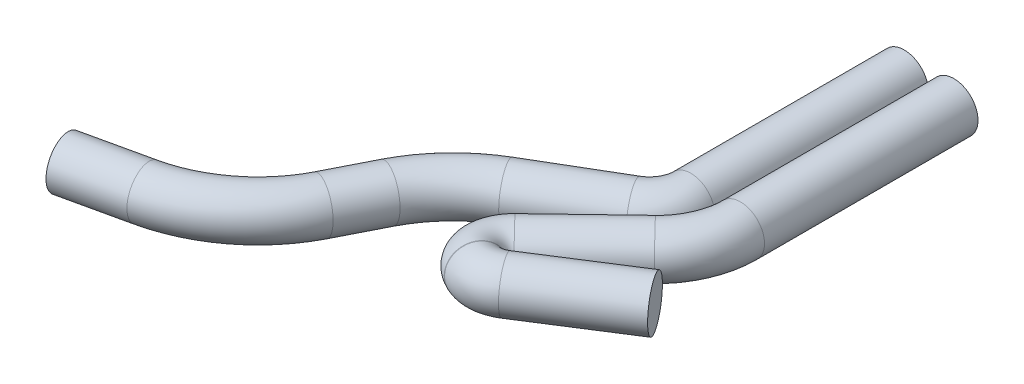
SolidWorks part; units mm, degrees
ref_plane "Plan de face" through (0, 0, 0) normal (0, 0, 1) x (1, 0, 0)
ref_plane "Plan de dessus" through (0, 0, 0) normal (0, 1, 0) x (1, 0, 0)
ref_plane "Plan de droite" through (0, 0, 0) normal (1, 0, 0) x (0, 0, -1)
sketch "Esquisse1" plane through (0, 0, 0) normal (0, 0, 1) x (1, 0, 0)
  line L0 (-1.8, 0) -> (1.8, 0) construction
  circle A0 centre (-1.8, 0) radius 1.75
  circle A1 centre (1.8, 0) radius 1.75
  dimension "D1" = 3.5
  dimension "D2" = 3.6
extrude "Boss.-Extru.1" add sketch "Esquisse1" along normal blind 5 and the other way blind 10
sketch3d "Esquisse3D1"
  line L0 (-27.1738, 2.5, 26.7093) -> (-27.282, 2.5, 26.2212) construction
  line L1 (-27.1738, 2.5, 26.7093) -> (-34.9842, 2.5, 28.4409) construction
  line L2 (11.0981, 2.5, 8.82) -> (4.351, 2.5, 13.1184)
  line L3 (4.351, -1.5, 13.1184) -> (11.0981, -1.5, 8.82)
  line L4 (4.6196, 2.5, 13.5401) -> (4.351, 2.5, 13.1184) construction
  line L5 (11.0981, -1.5, 8.82) -> (11.0981, 2.5, 8.82) construction
  line L6 (11.3667, -1.5, 9.2417) -> (4.6196, -1.5, 13.5401)
  line L7 (4.6196, 2.5, 13.5401) -> (11.3667, 2.5, 9.2417)
  line L8 (4.351, -1.5, 13.1184) -> (11.0981, -1.5, 8.82) construction
  line L9 (11.3667, -1.5, 9.2417) -> (4.6196, -1.5, 13.5401) construction
  line L10 (-35.0924, 2.5, 27.9527) -> (-27.282, 2.5, 26.2212)
  line L11 (-27.282, -1.5, 26.2212) -> (-35.0924, -1.5, 27.9527)
  line L14 (-34.9842, -1.5, 28.4409) -> (-27.1738, -1.5, 26.7093)
  line L15 (-27.1738, 2.5, 26.7093) -> (-34.9842, 2.5, 28.4409)
  arc A0 (-27.1738, -1.5, 26.7093) -> (-27.1738, 2.5, 26.7093) centre (-29.3568, 0.5, 27.1933) ccw construction
  arc A1 (4.351, 2.5, 13.1184) -> (4.351, -1.5, 13.1184) centre (6.2368, 0.5, 11.9169) ccw
  arc A2 (-27.282, 2.5, 26.2212) -> (-27.282, -1.5, 26.2212) centre (-29.4651, 0.5, 26.7052) ccw construction
  arc A3 (4.6196, 2.5, 13.5401) -> (4.6196, -1.5, 13.5401) centre (6.5055, 0.5, 12.3386) ccw
  arc A4 (4.6196, 2.5, 13.5401) -> (4.6196, -1.5, 13.5401) centre (6.5055, 0.5, 12.3386) ccw construction
  arc A5 (-27.282, 2.5, 26.2212) -> (-27.282, -1.5, 26.2212) centre (-29.4651, 0.5, 26.7052) ccw
  arc A6 (4.351, 2.5, 13.1184) -> (4.351, -1.5, 13.1184) centre (6.2368, 0.5, 11.9169) ccw construction
  arc A7 (-27.1738, -1.5, 26.7093) -> (-27.1738, 2.5, 26.7093) centre (-29.3568, 0.5, 27.1933) ccw
  arc A8 (11.0981, -1.5, 8.82) -> (11.6501, -1.5, 8.7717) centre (11.4205, -1.5, 9.326) ccw construction
  point P5 (7.8487, 0.5, 14.4471)
  point P11 (8.1174, 0.5, 14.8688)
  point P17 (-30.1144, 0.5, 23.7763)
  point P24 (-28.7075, 0.5, 30.1222)
  point P35 (-28.7075, 0.5, 30.1222)
  point P42 (-30.1144, 0.5, 23.7763)
  point P46 (8.1174, 0.5, 14.8688)
  point P50 (7.8487, 0.5, 14.4471)
  point P61 (11.4205, -2.1, 9.326)
sketch3d "Esquisse3D2"
  line L0 (1.8, 0, 5.5) -> (1.8, 0, 5)
  line L1 (6.2368, 0.5, 11.9169) -> (6.5055, 0.5, 12.3386) construction
  line L2 (6.3712, 0.5, 12.1278) -> (-2.7727, 0.5, 17.9531)
  line L3 (4.6196, 2.5, 13.5401) -> (11.3667, 2.5, 9.2417) construction
  line L4 (-4.8168, 0.3486, 18.0224) -> (-4.7698, 0.3552, 18.0468)
  line L5 (-0.0504, 0, 9.8337) -> (-5.2592, 0, 14.8212)
  line L6 (-4.2, 0, 5.5) -> (-0.0504, 0, 9.8337) construction
  line L7 (-4.2, 0, 5.5) -> (1.8, 0, 5.5) construction
  circle A0 centre (1.8, 0, 5) radius 1.75 construction
  arc A1 (-0.0504, 0, 9.8337) -> (1.8, 0, 5.5) centre (-4.2, 0, 5.5) ccw
  arc A2 (-2.7727, 0.5, 17.9531) -> (-4.7698, 0.3552, 18.0468) centre (-3.8361, 0.2118, 16.2839) ccw
  arc A3 (-4.8168, 0.3486, 18.0224) -> (-5.2592, 0, 14.8212) centre (-3.8881, 0.2639, 16.2531) ccw
  point P4 (1.8, 0, 6.75)
  point P17 (-4.2, 6, 5.5)
  point P19 (-3.7495, 0.5, 18.5754)
  point P20 (-3.6812, -1.7674, 16.527)
  point P23 (-7.2733, 0, 16.7497)
  point P24 (-3.7056, -1.7186, 16.4438)
  dimension "D1" = 6
  dimension "D2" = 12
  dimension "D4" = 4
  dimension "D6" = 2
  dimension "D3" = 0.5
  dimension "D5" = 10
sketch "Esquisse2" plane through (0, 0, 5) normal (0, 0, 1) x (1, 0, 0)
  circle A1 centre (1.8, 0) radius 1.75
  circle A2 centre (1.8, 0) radius 1.75
  dimension "D1" = 0
sweep "Balayage1" add profiles "Esquisse2" path "Esquisse3D2"
sketch "Esquisse3" plane through (-0.9639, 0, 0.6141) normal (0.8434, 0, -0.5373) x (-0.5373, 0, -0.8434)
  circle A1 centre (-13.6517, 0.5) radius 1.75
  circle A2 centre (-13.6517, 0.5) radius 1.75
  dimension "D1" = 0
extrude "Enlèv. mat.-Extru.1" cut sketch "Esquisse3" against normal blind 3
sketch3d "Esquisse3D3"
  line L0 (-1.8, 0, 5) -> (-1.8, 0, 5.5)
  line L1 (-3.2777, 0, 8.0851) -> (-9.1074, 0, 11.5182)
  line L2 (-29.3568, 0.5, 27.1933) -> (-29.4651, 0.5, 26.7052) construction
  line L3 (-29.411, 0.5, 26.9492) -> (-21.673, 0.5, 25.2338)
  line L4 (-35.0924, 2.5, 27.9527) -> (-27.282, 2.5, 26.2212) construction
  line L5 (-14.679, 0.2886, 19.4943) -> (-13.1949, 0.1348, 16.1179)
  circle A0 centre (-1.8, 0, 5) radius 1.75 construction
  arc A1 (-3.2777, 0, 8.0851) -> (-1.8, 0, 5.5) centre (-4.8, 0, 5.5) ccw
  arc A2 (-13.1949, 0.1348, 16.1179) -> (-9.1074, 0, 11.5182) centre (-4.0459, 0.7115, 20.1132) ccw
  arc A3 (-21.673, 0.5, 25.2338) -> (-14.679, 0.2886, 19.4943) centre (-23.8345, -0.0163, 15.4838) ccw
  point P4 (-1.8, 0, 6.75)
  point P8 (-1.8, 0, 7.2149)
  point P9 (-4.8, 3, 5.5)
  point P20 (-11.8945, 0, 13.1595)
  point P21 (-3.6848, -9.2632, 20.7263)
  point P24 (-16.7191, 0.5, 24.1355)
  point P25 (-23.9463, 9.9704, 14.9798)
  dimension "D1" = 3
  dimension "D6" = 10
  dimension "D7" = 10
  dimension "D2" = 0.5
  dimension "D3" = 13
  dimension "D4" = 10
  dimension "D5" = 12
sketch "Esquisse4" plane through (0, 0, 5) normal (0, 0, 1) x (1, 0, 0)
  circle A1 centre (-1.8, 0) radius 1.75
  circle A2 centre (-1.8, 0) radius 1.75
  dimension "D1" = 0
sweep "Balayage2" add profiles "Esquisse4" path "Esquisse3D3"
sketch "Esquisse5" plane through (-33.7278, 0, 7.4773) normal (-0.9763, 0, 0.2164) x (0.2164, 0, 0.9763)
  circle A1 centre (19.9447, 0.5) radius 1.75
  circle A2 centre (19.9447, 0.5) radius 1.75
  dimension "D1" = 0
extrude "Enlèv. mat.-Extru.2" cut sketch "Esquisse5" against normal blind 3
